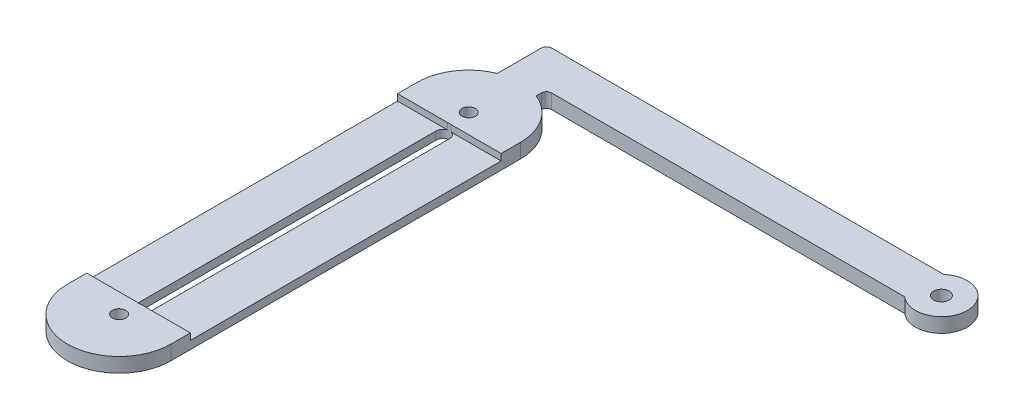
SolidWorks part; units mm, degrees
ref_plane "Front Plane" through (0, 0, 0) normal (0, 0, 1) x (1, 0, 0)
ref_plane "Top Plane" through (0, 0, 0) normal (0, 1, 0) x (1, 0, 0)
ref_plane "Right Plane" through (0, 0, 0) normal (1, 0, 0) x (0, 0, -1)
sketch "Sketch1" plane through (0, 0, 0) normal (0, 1, 0) x (1, 0, 0)
  line L0 (0, 85.725) -> (0, -85.725) construction
  line L1 (25.4, 85.725) -> (25.4, -85.725)
  line L2 (-25.4, 85.725) -> (-25.4, -85.725)
  line L3 (0, 73.025) -> (0, -73.025) construction
  line L4 (3.302, 73.025) -> (3.302, -73.025)
  line L5 (-3.302, 73.025) -> (-3.302, -73.025)
  arc A0 (25.4, 85.725) -> (-25.4, 85.725) centre (0, 85.725) ccw
  arc A1 (-25.4, -85.725) -> (25.4, -85.725) centre (0, -85.725) ccw
  arc A2 (3.302, 73.025) -> (-3.302, 73.025) centre (0, 73.025) ccw
  arc A3 (-3.302, -73.025) -> (3.302, -73.025) centre (0, -73.025) ccw
  circle A4 centre (0, 85.725) radius 3.302
  circle A5 centre (0, -85.725) radius 3.302
  point P3 (0, 0)
  point P10 (0, 0)
  dimension "D5" = 6.604
  dimension "D1" = 171.45
  dimension "D2" = 146.05
  dimension "D3" = 6.604
  dimension "D4" = 50.8
extrude "Boss-Extrude1" add sketch "Sketch1" along normal blind 7.112
sketch "Sketch2" plane through (0, 7.112, 0) normal (0, 1, 0) x (1, 0, 0)
  line L0 (25.4, -85.725) -> (25.4, 85.725) construction
  line L1 (25.4, 76.2) -> (-25.4, 76.2)
  line L2 (25.4, 76.2) -> (25.4, -76.2)
  line L3 (25.4, -76.2) -> (-25.4, -76.2)
  line L4 (-25.4, 76.2) -> (-25.4, -76.2)
  line L5 (-25.4, 85.725) -> (-25.4, -85.725) construction
  point P8 (25.4, 0)
  dimension "D1" = 152.4
extrude "Cut-Extrude1" cut sketch "Sketch2" against normal blind 3.175
sketch "Sketch3" plane through (0, 0, 0) normal (0, 1, 0) x (1, 0, 0)
  line L0 (-9.525, 85.725) -> (-9.525, 133.35)
  line L2 (9.525, 114.3) -> (9.525, 85.725)
  line L3 (-9.525, 85.725) -> (0, 95.25)
  line L4 (0, 95.25) -> (9.525, 85.725)
  line L5 (-9.525, 133.35) -> (185.2747, 133.35)
  line L8 (9.525, 114.3) -> (-9.525, 114.3) construction
  line L9 (9.525, 114.3) -> (9.525, 133.35) construction
  line L10 (185.2747, 114.3) -> (9.525, 114.3)
  line L11 (97.3999, 114.3) -> (97.3999, 133.35) construction
  line L12 (97.3999, 123.825) -> (193.675, 123.825) construction
  line L13 (0, 85.725) -> (0, 95.25) construction
  line L15 (0, 85.725) -> (-9.525, 85.725) construction
  line L16 (0, 85.725) -> (9.525, 85.725) construction
  arc A2 (185.2747, 114.3) -> (185.2747, 133.35) centre (193.675, 123.825) ccw
  circle A3 centre (193.675, 123.825) radius 3.81
  dimension "D2" = 7.62
  dimension "D1" = 38.1
  dimension "D3" = 25.4
  dimension "D4" = 203.2
  dimension "D5" = 19.05
extrude "Boss-Extrude2" add sketch "Sketch3" along normal up to surface (7.112 mm away) up to face at (0, 7.112, -83.6295)
fillet "Fillet1" radius 2.54 2 edges at (9.525, 3.556, -114.3) (-9.525, 3.556, -133.35)
